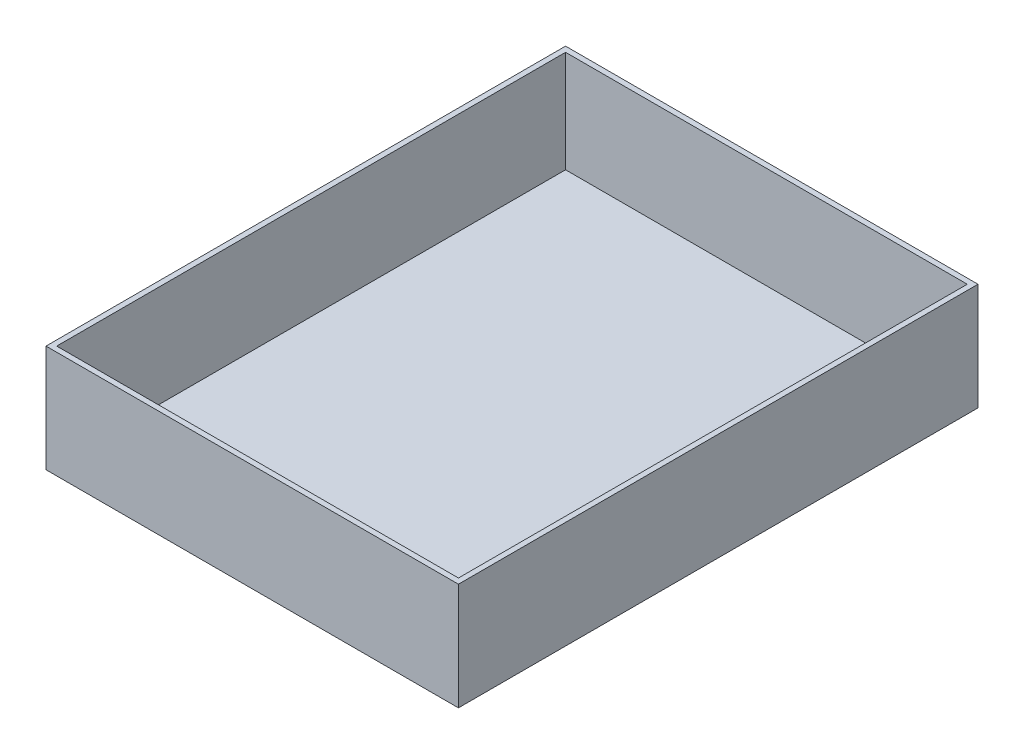
SolidWorks part; units mm, degrees
ref_plane "Front Plane" through (0, 0, 0) normal (0, 0, 1) x (1, 0, 0)
ref_plane "Top Plane" through (0, 0, 0) normal (0, 1, 0) x (1, 0, 0)
ref_plane "Right Plane" through (0, 0, 0) normal (1, 0, 0) x (0, 0, -1)
sketch "Sketch1" plane through (0, 0, 0) normal (0, 1, 0) x (1, 0, 0)
  line L1 (-95.25, 120.65) -> (95.25, 120.65)
  line L2 (-95.25, 120.65) -> (-95.25, -120.65)
  line L3 (-95.25, -120.65) -> (95.25, -120.65)
  line L4 (95.25, 120.65) -> (95.25, -120.65)
  point P4 (-95.25, 0)
  point P6 (0, 120.65)
  dimension "D1" = 241.3
  dimension "D2" = 190.5
extrude "Boss-Extrude1" add sketch "Sketch1" along normal blind 2.54
sketch "Sketch2" plane through (0, 0, 0) normal (0, -1, 0) x (1, 0, 0)
  line L0 (95.25, 120.65) -> (95.25, -120.65) construction
  line L1 (-95.25, 120.65) -> (95.25, 120.65)
  line L2 (-95.25, 120.65) -> (-95.25, -120.65)
  line L3 (-95.25, -120.65) -> (95.25, -120.65)
  line L4 (95.25, 120.65) -> (95.25, -120.65)
  line L5 (-97.79, 123.19) -> (97.79, 123.19)
  line L6 (-97.79, 123.19) -> (-97.79, -123.19)
  line L7 (-97.79, -123.19) -> (97.79, -123.19)
  line L8 (97.79, 123.19) -> (97.79, -123.19)
  line L9 (95.25, -120.65) -> (-95.25, -120.65) construction
  point P9 (0, 123.19)
  point P11 (-97.79, 0)
  dimension "D1" = 2.54
  dimension "D2" = 2.54
extrude "Boss-Extrude2" add sketch "Sketch2" against normal blind 50.8
